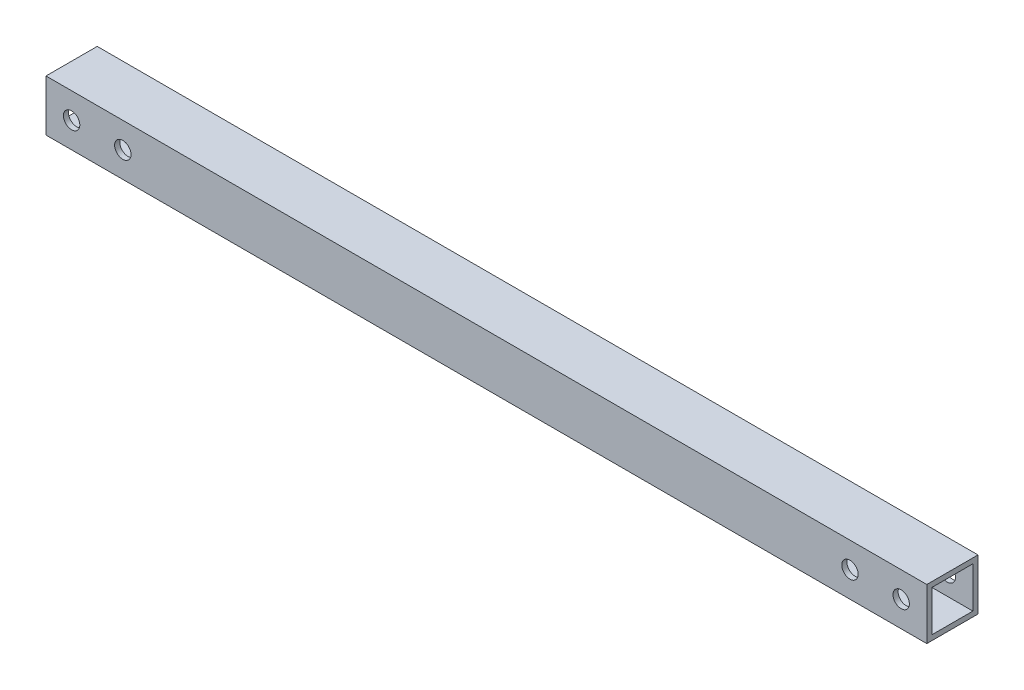
SolidWorks part; units mm, degrees
material "5052-H34"
ref_plane "正面" through (0, 0, 0) normal (0, 0, 1) x (1, 0, 0)
ref_plane "平面" through (0, 0, 0) normal (0, 1, 0) x (1, 0, 0)
ref_plane "右側面" through (0, 0, 0) normal (1, 0, 0) x (0, 0, -1)
sketch "ｽｹｯﾁ1" plane through (0, 0, 0) normal (1, 0, 0) x (0, 0, -1)
  line L1 (-5, 5) -> (5, 5)
  line L2 (-5, 5) -> (-5, -5)
  line L3 (-5, -5) -> (5, -5)
  line L4 (5, 5) -> (5, -5)
  line L5 (-5, 5) -> (5, -5) construction
  line L6 (-5, -5) -> (5, 5) construction
  point P0 (0, 0)
  dimension "D1" = 10
extrude "押し出し-薄板1" add sketch "ｽｹｯﾁ1" along normal blind 172 thin
sketch "ｽｹｯﾁ2" plane through (0, 0, 5) normal (0, 0, 1) x (1, 0, 0)
  line L0 (86, 5) -> (86, -5) construction
  line L1 (172, 5) -> (0, 5) construction
  line L2 (172, -5) -> (0, -5) construction
  line L3 (0, 0) -> (15, 0) construction
  line L4 (0, 5) -> (0, -5) construction
  circle A0 centre (15, 0) radius 1.6
  circle A1 centre (5, 0) radius 1.6
  circle A2 centre (167, 0) radius 1.6
  circle A3 centre (157, 0) radius 1.6
  dimension "D3" = 3.2
  dimension "D1" = 5
  dimension "D2" = 10
extrude "ｶｯﾄ - 押し出し1" cut sketch "ｽｹｯﾁ2" against normal through all
